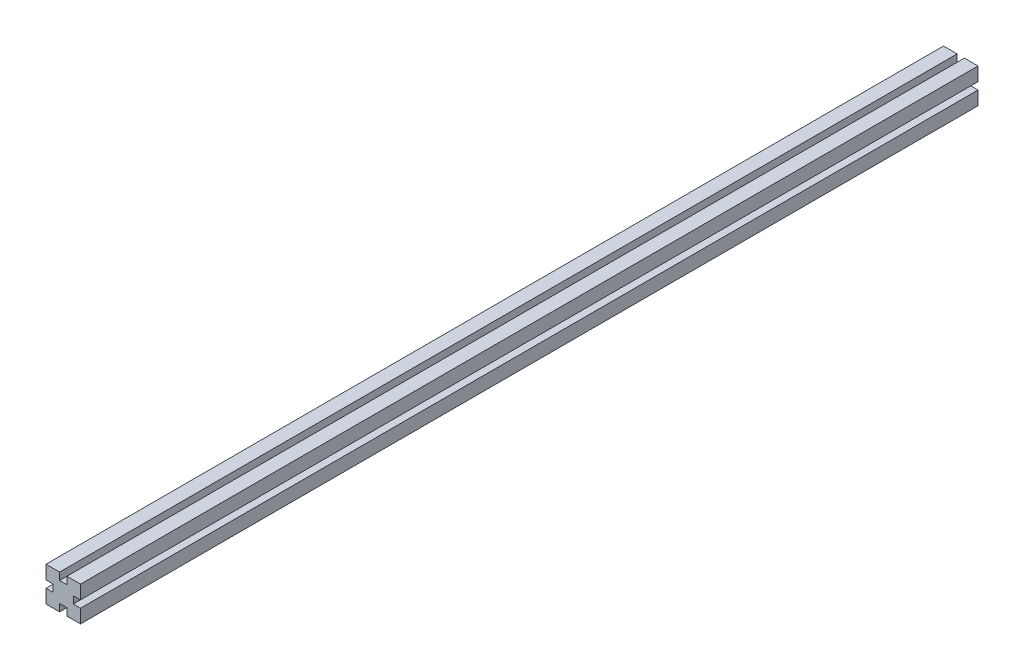
SolidWorks part; units mm, degrees
ref_plane "Front Plane" through (0, 0, 0) normal (0, 0, 1) x (1, 0, 0)
ref_plane "Top Plane" through (0, 0, 0) normal (0, 1, 0) x (1, 0, 0)
ref_plane "Right Plane" through (0, 0, 0) normal (1, 0, 0) x (0, 0, -1)
sketch "Sketch1" plane through (0, 0, 0) normal (0, 0, 1) x (1, 0, 0)
  line L0 (-19.05, -19.05) -> (-4, -19.05)
  line L1 (-4, -19.05) -> (-4, -11.05)
  line L2 (-4, -11.05) -> (4, -11.05)
  line L3 (4, -11.05) -> (4, -19.05)
  line L4 (4, -19.05) -> (19.05, -19.05)
  line L5 (19.05, -19.05) -> (19.05, -4)
  line L6 (19.05, -4) -> (11.05, -4)
  line L7 (11.05, -4) -> (11.05, 4)
  line L8 (11.05, 4) -> (19.05, 4)
  line L9 (19.05, 4) -> (19.05, 19.05)
  line L10 (19.05, 19.05) -> (4, 19.05)
  line L11 (4, 19.05) -> (4, 11.05)
  line L12 (4, 11.05) -> (-4, 11.05)
  line L13 (-4, 11.05) -> (-4, 19.05)
  line L14 (-4, 19.05) -> (-19.05, 19.05)
  line L15 (-19.05, 19.05) -> (-19.05, 4)
  line L16 (-19.05, 4) -> (-11.05, 4)
  line L17 (-11.05, 4) -> (-11.05, -4)
  line L18 (-11.05, -4) -> (-19.05, -4)
  line L19 (-19.05, -4) -> (-19.05, -19.05)
extrude "Profile" add sketch "Sketch1" along normal blind 991.11
equation "\"length\" = 991.11mm"
equation "\"D1@Profile\" = \"length\""
